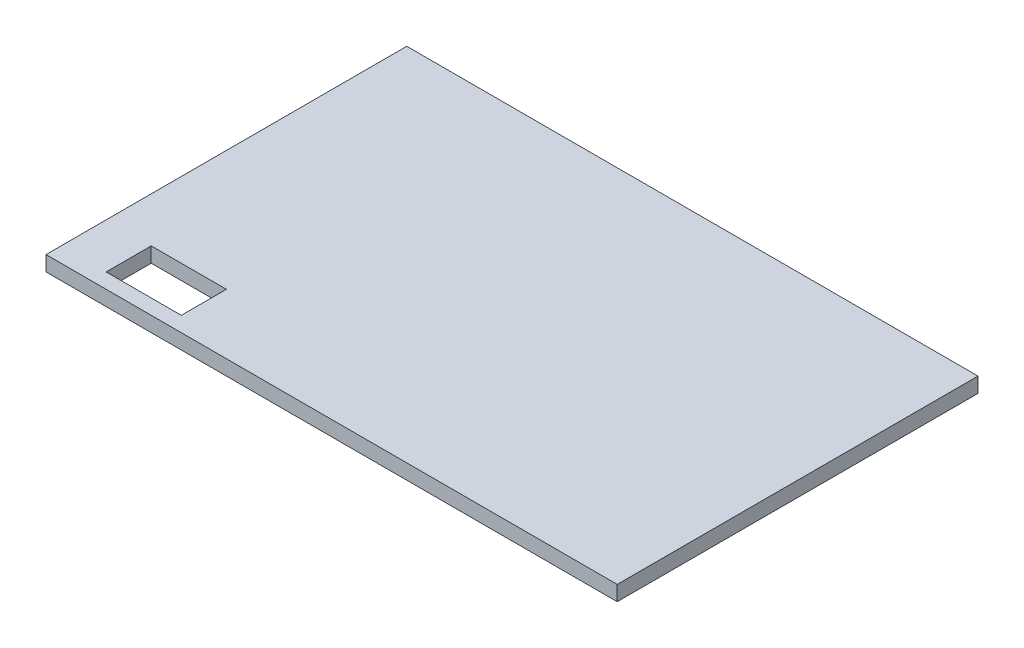
SolidWorks part; units mm, degrees
ref_plane "Front Plane" through (0, 0, 0) normal (0, 0, 1) x (1, 0, 0)
ref_plane "Top Plane" through (0, 0, 0) normal (0, 1, 0) x (1, 0, 0)
ref_plane "Right Plane" through (0, 0, 0) normal (1, 0, 0) x (0, 0, -1)
sketch "Sketch1" plane through (0, 0, 0) normal (0, 1, 0) x (1, 0, 0)
  line L1 (0, 0) -> (40, 0)
  line L2 (0, 0) -> (0, 24)
  line L3 (0, 24) -> (40, 24)
  line L4 (40, 0) -> (40, 24)
  dimension "D1" = 40
  dimension "D2" = 24
extrude "Boss-Extrude1" add sketch "Sketch1" along normal blind 2
sketch "Sketch2" plane through (0, 2, 0) normal (0, 1, 0) x (1, 0, 0)
  line L1 (3, 1) -> (39, 1)
  line L2 (3, 1) -> (3, 23)
  line L3 (3, 23) -> (39, 23)
  line L4 (39, 1) -> (39, 23)
  line L5 (0, 24) -> (40, 24)
  line L6 (0, 24) -> (0, 0)
  line L7 (0, 0) -> (40, 0)
  line L8 (40, 24) -> (40, 0)
  dimension "D1" = 22
  dimension "D2" = 36
  dimension "D3" = 1
  dimension "D4" = 1
extrude "Boss-Extrude3" add sketch "Sketch2" along normal blind 8
sketch "Sketch5" plane through (0, 2, 0) normal (0, 1, 0) x (1, 0, 0)
  line L0 (3, 1) -> (39, 1) construction
  line L1 (4, 1) -> (8, 1)
  line L2 (4, 1) -> (4, 4)
  line L3 (4, 4) -> (8, 4)
  line L4 (8, 1) -> (8, 4)
  line L6 (3, 23) -> (3, 1) construction
  dimension "D1" = 1
  dimension "D2" = 4
  dimension "D3" = 3
extrude "Cut-Extrude1" cut sketch "Sketch5" against normal blind 2
sketch "Sketch6" plane through (40, 0, 0) normal (1, 0, 0) x (0, 0, -1)
  line L1 (0, 10) -> (24, 10)
  line L2 (0, 10) -> (0, 0)
  line L3 (0, 0) -> (24, 0)
  line L4 (24, 10) -> (24, 0)
extrude "Cut-Extrude2" cut sketch "Sketch6" against normal blind 2
sketch "Sketch7" plane through (3, 0, 0) normal (1, 0, 0) x (0, 0, -1)
  line L1 (1, 2) -> (23, 2)
  line L2 (1, 2) -> (1, 10)
  line L3 (1, 10) -> (23, 10)
  line L4 (23, 2) -> (23, 10)
extrude "Cut-Extrude3" cut sketch "Sketch7" against normal blind 2
sketch "Sketch8" plane through (0, 2, 0) normal (0, 1, 0) x (1, 0, 0)
  line L0 (1, 1) -> (4, 1) construction
  line L1 (4, 4) -> (3, 4)
  line L2 (4, 4) -> (4, 1)
  line L3 (4, 1) -> (3, 1)
  line L4 (3, 4) -> (3, 1)
  dimension "D1" = 1
extrude "Cut-Extrude4" cut sketch "Sketch8" against normal blind 2
sketch "Sketch9" plane through (0, 10, 0) normal (0, 1, 0) x (1, 0, 0)
  line L1 (0, 24) -> (38, 24)
  line L2 (0, 24) -> (0, 0)
  line L3 (0, 0) -> (38, 0)
  line L4 (38, 24) -> (38, 0)
extrude "Cut-Extrude5" cut sketch "Sketch9" against normal blind 9
